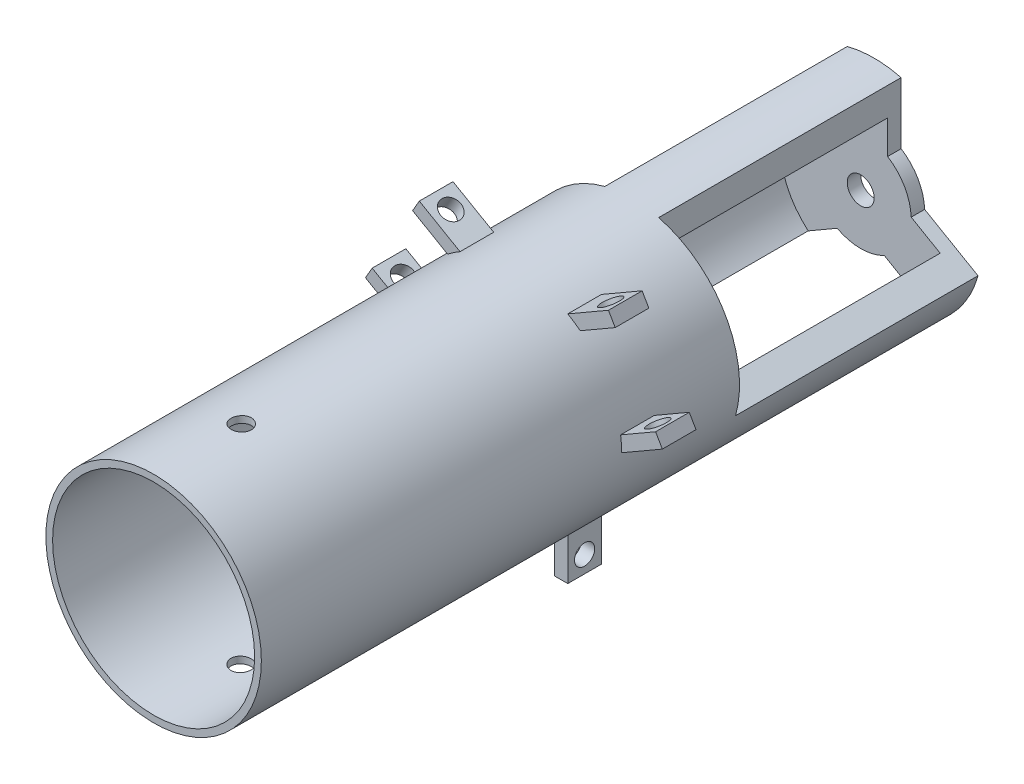
SolidWorks part; units mm, degrees
material "ABS"
ref_plane "Front Plane" through (0, 0, 0) normal (0, 0, 1) x (1, 0, 0)
ref_plane "Top Plane" through (0, 0, 0) normal (0, 1, 0) x (1, 0, 0)
ref_plane "Right Plane" through (0, 0, 0) normal (1, 0, 0) x (0, 0, -1)
sketch "Sketch1" plane through (0, 0, 0) normal (0, 0, 1) x (1, 0, 0)
  circle A0 centre (0, 0) radius 15
  circle A1 centre (0, 0) radius 16
  dimension "D1" = 30
  dimension "D2" = 32
extrude "Boss-Extrude1" add sketch "Sketch1" along normal blind 70
ref_plane "Plane1" through (-16, 0, 0) normal (-1, 0, 0) x (0, 0, 1)
sketch "Sketch2" plane through (-16, 0, 0) normal (-1, 0, 0) x (0, 0, 1)
  line L0 (70, -16) -> (70, 16) construction
  line L1 (70, 16) -> (0, 16) construction
  circle A0 centre (50, -5) radius 6.5
  dimension "D1" = 13
  dimension "D2" = 20
  dimension "D3" = 21
extrude "Cut-Extrude1" [suppressed] cut sketch "Sketch2" against normal through all
sketch "Sketch3" plane through (0, 0, 0) normal (0, 0, -1) x (-1, 0, 0)
  circle A0 centre (0, 0) radius 16
  dimension "D1" = 32
extrude "Boss-Extrude2" add sketch "Sketch3" along normal blind 1
sketch "Sketch4" plane through (0, 0, -1) normal (0, 0, -1) x (-1, 0, 0)
  circle A2 centre (0, 0) radius 6.5
  dimension "D1" = 13
extrude "Cut-Extrude2" cut sketch "Sketch4" against normal up to next
sketch "Sketch5" plane through (0, 0, -1) normal (0, 0, -1) x (-1, 0, 0)
  line L0 (0, 0) -> (0, 34.4859) construction
  line L1 (-4, 15.4919) -> (-4, 11.3137)
  line L2 (4, 15.4919) -> (4, 11.3137)
  line L3 (15.4164, -4.2819) -> (11.798, -2.1928)
  line L4 (11.4164, -11.2101) -> (7.798, -9.121)
  line L5 (-11.4164, -11.2101) -> (-7.798, -9.121)
  line L6 (-15.4164, -4.2819) -> (-11.798, -2.1928)
  arc A0 (-11.798, -2.1928) -> (-7.798, -9.121) centre (0, 0) ccw
  arc A1 (-15.4164, -4.2819) -> (-11.4164, -11.2101) centre (0, 0) ccw
  arc A2 (4, 11.3137) -> (-4, 11.3137) centre (0, 0) ccw
  arc A3 (4, 15.4919) -> (-4, 15.4919) centre (0, 0) ccw
  arc A4 (7.798, -9.121) -> (11.798, -2.1928) centre (0, 0) ccw
  arc A5 (11.4164, -11.2101) -> (15.4164, -4.2819) centre (0, 0) ccw
  dimension "D1" = 24
  dimension "D2" = 32
  dimension "D3" = 8
  dimension "D4" = 3
extrude "Boss-Extrude3" add sketch "Sketch5" along normal blind 34
sketch "Sketch6" plane through (0, 0, -35) normal (0, 0, -1) x (-1, 0, 0)
  line L0 (-4, 15.4919) -> (-4, 6.3443)
  line L1 (4, 15.4919) -> (4, 6.3443)
  line L2 (15.4164, -4.2819) -> (7.4943, 0.292)
  line L3 (11.4164, -11.2101) -> (3.4943, -6.6362)
  line L4 (-11.4164, -11.2101) -> (-3.4943, -6.6362)
  line L5 (-15.4164, -4.2819) -> (-7.4943, 0.292)
  arc A0 (-15.4164, -4.2819) -> (-11.4164, -11.2101) centre (0, 0) ccw
  arc A1 (-3.4943, -6.6362) -> (3.4943, -6.6362) centre (0, 0) ccw
  arc A2 (4, 15.4919) -> (-4, 15.4919) centre (0, 0) ccw
  arc A3 (11.4164, -11.2101) -> (15.4164, -4.2819) centre (0, 0) ccw
  arc A4 (7.4943, 0.292) -> (4, 6.3443) centre (0, 0) ccw
  arc A5 (-4, 6.3443) -> (-7.4943, 0.292) centre (0, 0) ccw
  circle A6 centre (0, 0) radius 2
  dimension "D1" = 32
  dimension "D2" = 15
  dimension "D7" = 4
  dimension "D3" = 8
  dimension "D4" = 8
  dimension "D5" = 120
  dimension "D6" = 120
  dimension "D8" = 8
extrude "Boss-Extrude4" add sketch "Sketch6" along normal blind 2
ref_plane "Plane2" through (0, 0, 14) normal (0, 0, -1) x (-1, 0, 0)
sketch "Sketch7" plane through (0, 0, 14) normal (0, 0, -1) x (-1, 0, 0)
  line L0 (0, 0) -> (0, 33.8196) construction
  line L1 (0, 0) -> (49.5298, 28.596) construction
  line L2 (15.0414, 15.6124) -> (9.8452, 12.6124)
  line L3 (15.0414, 15.6124) -> (14.0414, 17.3444)
  line L4 (14.0414, 17.3444) -> (8, 13.8564)
  line L5 (21.0414, 5.22) -> (22.0414, 3.488)
  line L6 (22.0414, 3.488) -> (16, 0)
  line L7 (21.0414, 5.22) -> (15.8452, 2.22)
  arc A0 (9.8452, 12.6124) -> (8, 13.8564) centre (0, 0) ccw
  arc A1 (16, 0) -> (15.8452, 2.22) centre (0, 0) ccw
  point P7 (11.0207, 15.6004)
  dimension "D5" = 32
  dimension "D1" = 60
  dimension "D2" = 2
  dimension "D3" = 6
  dimension "D4" = 12
extrude "Boss-Extrude5" add sketch "Sketch7" along normal mid plane 5
sketch "Sketch8" plane through (-4, -6.9282, 0) normal (-0.5, -0.866, 0) x (0.866, -0.5, 0)
  line L0 (-22.8885, 14) -> (22.8885, 14) construction
  line L1 (-20.8324, 11.5) -> (-20.8324, 16.5) construction
  circle A0 centre (-18.3324, 14) radius 1.5
  point P8 (-20.8324, 14)
  dimension "D1" = 3
  dimension "D2" = 2.5
extrude "Cut-Extrude3" cut sketch "Sketch8" against normal through all
pattern_circular "CirPattern1" count 3 over 360 about axis through (0, 0, 0) along (0, 0, 1) of "Boss-Extrude5", "Cut-Extrude3"
sketch "Sketch9" plane through (0, 0, -1) normal (0, 0, -1) x (-1, 0, 0)
  line L0 (0, 0) -> (0, 18.4664) construction
  circle A0 centre (-12.5, 0) radius 1.5
  circle A1 centre (12.5, 0) radius 1.5
  dimension "D2" = 3
  dimension "D3" = 3
  dimension "D1" = 25
extrude "Cut-Extrude4" cut sketch "Sketch9" against normal through all
ref_plane "Plane3" through (0, 0, 57) normal (0, 0, 1) x (1, 0, 0)
sketch "Sketch10" plane through (0, 0, 57) normal (0, 0, 1) x (1, 0, 0)
  line L0 (0, 0) -> (0, 39.7944) construction
  line L1 (0, 20) -> (1.5, 20)
  line L2 (1.5, 20) -> (1.5, -20)
  line L3 (1.5, -20) -> (0, -20)
  line L4 (0, 20) -> (0, -20)
  line L5 (0, 0) -> (-40.1753, 0) construction
  dimension "D1" = 40
  dimension "D2" = 3
revolve "Cut-Revolve1" cut sketch "Sketch10" angle 360 about L0
